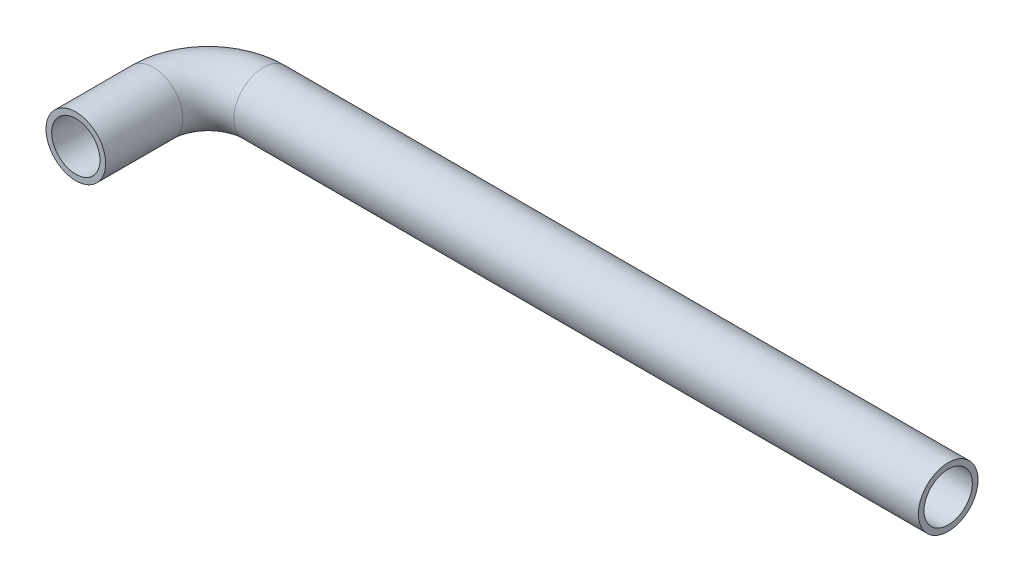
SolidWorks part; units mm, degrees
ref_plane "Front Plane" through (0, 0, 0) normal (0, 0, 1) x (1, 0, 0)
ref_plane "Top Plane" through (0, 0, 0) normal (0, 1, 0) x (1, 0, 0)
ref_plane "Right Plane" through (0, 0, 0) normal (1, 0, 0) x (0, 0, -1)
sketch "Sketch2" plane through (0, 0, 0) normal (0, 0, 1) x (1, 0, 0)
  circle A0 centre (0, 0) radius 5.5562
  circle A1 centre (0, 0) radius 6.858
  dimension "D1" = 13.716
  dimension "D2" = 11.1125
sketch "Sketch6" plane through (0, 0, 0) normal (0, 1, 0) x (1, 0, 0)
  line L0 (0, 0) -> (0, 17.78)
  line L1 (12.7, 30.48) -> (170.18, 30.48)
  line L4 (23.114, 156.21) -> (23.114, 184.0952) construction
  arc A0 (0, 17.78) -> (12.7, 30.48) centre (12.7, 17.78) cw
  dimension "D2" = 12.7
  dimension "D1" = 17.78
  dimension "D3" = 157.48
sweep "Sweep5" add profiles "Sketch2" path "Sketch6"
